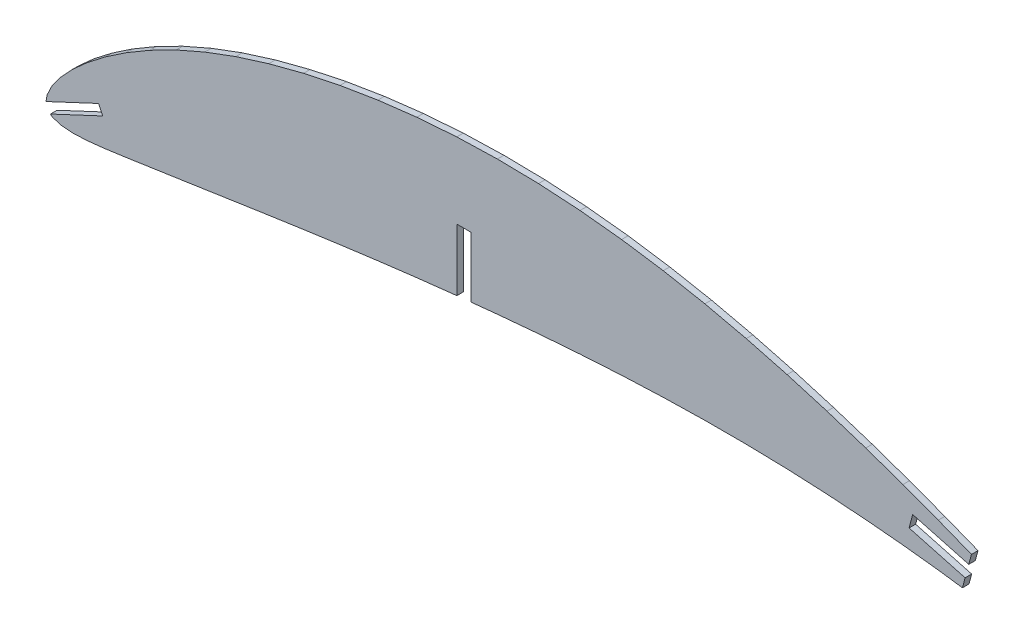
SolidWorks part; units mm, degrees
ref_plane "Front Plane" through (0, 0, 0) normal (0, 0, 1) x (1, 0, 0)
ref_plane "Top Plane" through (0, 0, 0) normal (0, 1, 0) x (1, 0, 0)
ref_plane "Right Plane" through (0, 0, 0) normal (1, 0, 0) x (0, 0, -1)
sketch "Model" plane through (0, 0, 0) normal (0, 0, 1) x (1, 0, 0)
  line L0 (-3.0277, -1.0909) -> (-2.3414, -1.021)
  line L1 (9.74, -0.8757) -> (9.6703, -1.134)
  line L2 (8.3857, -0.1371) -> (8.2919, -0.4847)
  line L3 (9.74, -0.8757) -> (8.2919, -0.4847)
  line L4 (9.8339, -0.5281) -> (8.3857, -0.1371)
  line L5 (9.9036, -0.2698) -> (9.8339, -0.5281)
  line L6 (-3.0277, 0.472) -> (-3.0277, -1.0909)
  line L7 (-3.3877, 0.472) -> (-3.0277, 0.472)
  line L8 (-1.2782, 2.4333) -> (-2.3414, 2.4513)
  line L9 (-11.3187, 0.3949) -> (-11.9294, 0.0351)
  line L10 (-0.2058, 2.3678) -> (-1.2782, 2.4333)
  line L11 (-10.6403, 0.741) -> (-11.3187, 0.3949)
  line L12 (0.8677, 2.2547) -> (-0.2058, 2.3678)
  line L13 (-9.8986, 1.0655) -> (-10.6403, 0.741)
  line L14 (1.9424, 2.0957) -> (0.8677, 2.2547)
  line L15 (-9.0989, 1.3635) -> (-9.8986, 1.0655)
  line L16 (3.0178, 1.8921) -> (1.9424, 2.0957)
  line L17 (-8.2463, 1.6309) -> (-9.0989, 1.3635)
  line L18 (4.0863, 1.6488) -> (3.0178, 1.8921)
  line L19 (-7.3472, 1.8655) -> (-8.2463, 1.6309)
  line L20 (5.1405, 1.3716) -> (4.0863, 1.6488)
  line L21 (-6.4064, 2.0646) -> (-7.3472, 1.8655)
  line L22 (6.172, 1.0675) -> (5.1405, 1.3716)
  line L23 (-5.4295, 2.2256) -> (-6.4064, 2.0646)
  line L24 (7.1725, 0.7441) -> (6.172, 1.0675)
  line L25 (-4.4229, 2.3454) -> (-5.4295, 2.2256)
  line L26 (8.1334, 0.4078) -> (7.1725, 0.7441)
  line L27 (-3.3916, 2.4213) -> (-4.4229, 2.3454)
  line L28 (9.0465, 0.0671) -> (8.1334, 0.4078)
  line L29 (-2.3414, 2.4513) -> (-3.3916, 2.4213)
  line L30 (9.9036, -0.2698) -> (9.0465, 0.0671)
  line L31 (-11.9294, 0.0351) -> (-12.469, -0.3286)
  line L32 (-12.469, -0.3286) -> (-12.9329, -0.687)
  line L33 (-12.9329, -0.687) -> (-13.3188, -1.0339)
  line L34 (-13.3188, -1.0339) -> (-13.6254, -1.3637)
  line L35 (-13.6254, -1.3637) -> (-13.8466, -1.6673)
  line L36 (-13.8466, -1.6673) -> (-13.9726, -1.9319)
  line L37 (-1.2782, -0.9261) -> (-0.2058, -0.8455)
  line L38 (-0.2058, -0.8455) -> (0.8677, -0.7819)
  line L39 (0.8677, -0.7819) -> (1.9424, -0.7377)
  line L40 (1.9424, -0.7377) -> (3.0178, -0.7147)
  line L41 (3.0178, -0.7147) -> (4.0863, -0.715)
  line L42 (4.0863, -0.715) -> (5.1405, -0.7393)
  line L43 (5.1405, -0.7393) -> (6.172, -0.7878)
  line L44 (6.172, -0.7878) -> (7.1725, -0.8575)
  line L45 (7.1725, -0.8575) -> (8.1334, -0.9457)
  line L46 (8.1334, -0.9457) -> (9.0465, -1.049)
  line L47 (-3.3877, -1.128) -> (-3.3877, 0.472)
  line L48 (-12.5354, -1.6827) -> (-13.8837, -2.3136)
  line L49 (-12.6414, -1.4562) -> (-12.5354, -1.6827)
  line L50 (-14, -2.092) -> (-12.6414, -1.4562)
  line L51 (-14, -2.0959) -> (-13.9992, -2.0959)
  line L52 (9.0465, -1.049) -> (9.6703, -1.134)
  line L53 (-2.3414, -1.021) -> (-1.2782, -0.9261)
  line L54 (-3.3916, -1.128) -> (-3.3877, -1.128)
  line L55 (-4.419, -1.2447) -> (-3.3877, -1.128)
  line L56 (-5.4295, -1.3688) -> (-4.4229, -1.2447)
  line L57 (-6.4064, -1.4979) -> (-5.4295, -1.3688)
  line L58 (-7.3472, -1.6292) -> (-6.4064, -1.4979)
  line L59 (-8.2463, -1.7597) -> (-7.3472, -1.6292)
  line L60 (-9.0989, -1.8865) -> (-8.2463, -1.7597)
  line L61 (-9.8986, -2.0063) -> (-9.0989, -1.8865)
  line L62 (-10.6403, -2.1172) -> (-9.8986, -2.0063)
  line L63 (-11.3187, -2.2177) -> (-10.6403, -2.1172)
  line L64 (-11.9294, -2.3085) -> (-11.3187, -2.2177)
  line L65 (-12.469, -2.3838) -> (-11.9294, -2.3085)
  line L66 (-12.9329, -2.4345) -> (-12.469, -2.3838)
  line L67 (-13.3188, -2.4513) -> (-12.9329, -2.4345)
  line L68 (-13.6254, -2.4261) -> (-13.3188, -2.4513)
  line L69 (-13.8466, -2.3519) -> (-13.6254, -2.4261)
  line L70 (-13.8837, -2.3136) -> (-13.8466, -2.3519)
  line L71 (-14, -2.092) -> (-13.9992, -2.0959)
  line L72 (-13.9726, -1.9319) -> (-14, -2.092)
sketch "Sketch3" plane through (0, 0, 0) normal (0, 0, 1) x (1, 0, 0)
  line L72 (-14.9371, 2.21) -> (-15.2622, 0.3121)
  line L73 (86.2984, 8.8825) -> (98.2266, 10.3524)
  line L74 (74.7219, 7.3529) -> (86.2984, 8.8825)
  line L75 (63.5735, 5.7968) -> (74.7219, 7.3529)
  line L76 (52.9194, 4.2506) -> (63.5735, 5.7968)
  line L77 (42.816, 2.7475) -> (52.9194, 4.2506)
  line L78 (33.3398, 1.3274) -> (42.816, 2.7475)
  line L79 (24.5505, 0.0135) -> (33.3398, 1.3274)
  line L80 (16.5109, -1.1777) -> (24.5505, 0.0135)
  line L81 (9.2744, -2.2527) -> (16.5109, -1.1777)
  line L82 (2.8806, -3.1452) -> (9.2744, -2.2527)
  line L83 (-2.6173, -3.7458) -> (2.8806, -3.1452)
  line L84 (-7.1895, -3.9449) -> (-2.6173, -3.7458)
  line L85 (-10.8227, -3.6463) -> (-7.1895, -3.9449)
  line L86 (-13.444, -2.767) -> (-10.8227, -3.6463)
  line L87 (-13.8837, -2.3136) -> (-13.444, -2.767)
  line L88 (2.0927, 5.1631) -> (-13.8837, -2.3136)
  line L89 (0.837, 7.8463) -> (2.0927, 5.1631)
  line L90 (-15.2622, 0.3121) -> (0.837, 7.8463)
  line L91 (98.2728, 10.3524) -> (110.493, 11.736)
  line L92 (110.4468, 11.736) -> (110.493, 11.736)
  line L93 (98.2266, 10.3524) -> (98.2728, 10.3524)
  line L95 (110.493, 11.736) -> (110.493, 30.696)
  line L96 (110.493, 30.696) -> (114.759, 30.696)
  line L97 (114.759, 30.696) -> (114.759, 12.1751)
  line L98 (114.759, 12.1751) -> (122.8927, 13.0035)
  line L99 (122.8927, 13.0035) -> (135.4911, 14.1283)
  line L100 (135.4911, 14.1283) -> (148.199, 15.0839)
  line L101 (148.199, 15.0839) -> (160.9203, 15.837)
  line L102 (160.9203, 15.837) -> (173.6547, 16.3613)
  line L103 (173.6547, 16.3613) -> (186.3992, 16.6334)
  line L104 (186.3992, 16.6334) -> (199.0607, 16.63)
  line L105 (199.0607, 16.63) -> (211.5529, 16.3414)
  line L106 (211.5529, 16.3414) -> (223.7765, 15.7674)
  line L107 (223.7765, 15.7674) -> (235.6317, 14.9412)
  line L108 (235.6317, 14.9412) -> (247.019, 13.896)
  line L109 (247.019, 13.896) -> (257.839, 12.6717)
  line L110 (257.839, 12.6717) -> (265.2306, 11.6647)
  line L111 (266.057, 14.7259) -> (265.2306, 11.6647)
  line L112 (266.057, 14.7259) -> (248.8965, 19.359)
  line L113 (250.0084, 23.4775) -> (248.8965, 19.359)
  line L114 (267.169, 18.8445) -> (250.0084, 23.4775)
  line L115 (267.9954, 21.9057) -> (267.169, 18.8445)
  line L116 (267.9954, 21.9057) -> (257.839, 25.8972)
  line L117 (257.839, 25.8972) -> (247.019, 29.9352)
  line L118 (247.019, 29.9352) -> (235.6317, 33.9201)
  line L119 (235.6317, 33.9201) -> (223.7765, 37.7524)
  line L120 (223.7765, 37.7524) -> (211.5529, 41.3558)
  line L121 (211.5529, 41.3558) -> (199.0607, 44.6406)
  line L122 (199.0607, 44.6406) -> (186.3992, 47.5239)
  line L123 (186.3992, 47.5239) -> (173.6547, 49.9361)
  line L124 (173.6547, 49.9361) -> (160.9203, 51.8207)
  line L125 (160.9203, 51.8207) -> (148.199, 53.1612)
  line L126 (148.199, 53.1612) -> (135.4911, 53.9376)
  line L127 (135.4911, 53.9376) -> (122.8927, 54.15)
  line L128 (122.8927, 54.15) -> (110.4468, 53.795)
  line L129 (110.4468, 53.795) -> (98.2266, 52.8958)
  line L130 (98.2266, 52.8958) -> (86.2984, 51.4757)
  line L131 (86.2984, 51.4757) -> (74.7219, 49.5678)
  line L132 (74.7219, 49.5678) -> (63.5735, 47.2087)
  line L133 (63.5735, 47.2087) -> (52.9194, 44.4282)
  line L134 (52.9194, 44.4282) -> (42.816, 41.2596)
  line L135 (42.816, 41.2596) -> (33.3398, 37.7292)
  line L136 (33.3398, 37.7292) -> (24.5505, 33.8836)
  line L137 (24.5505, 33.8836) -> (16.5109, 29.7826)
  line L138 (16.5109, 29.7826) -> (9.2744, 25.519)
  line L139 (9.2744, 25.519) -> (2.8806, 21.2089)
  line L140 (2.8806, 21.2089) -> (-2.6173, 16.9618)
  line L141 (-2.6173, 16.9618) -> (-7.1895, 12.8508)
  line L142 (-7.1895, 12.8508) -> (-10.8227, 8.9422)
  line L143 (-10.8227, 8.9422) -> (-13.444, 5.3455)
  line L144 (-13.444, 5.3455) -> (-14.9371, 2.21)
extrude "Boss-Extrude1" add sketch "Sketch3" along normal blind 2
